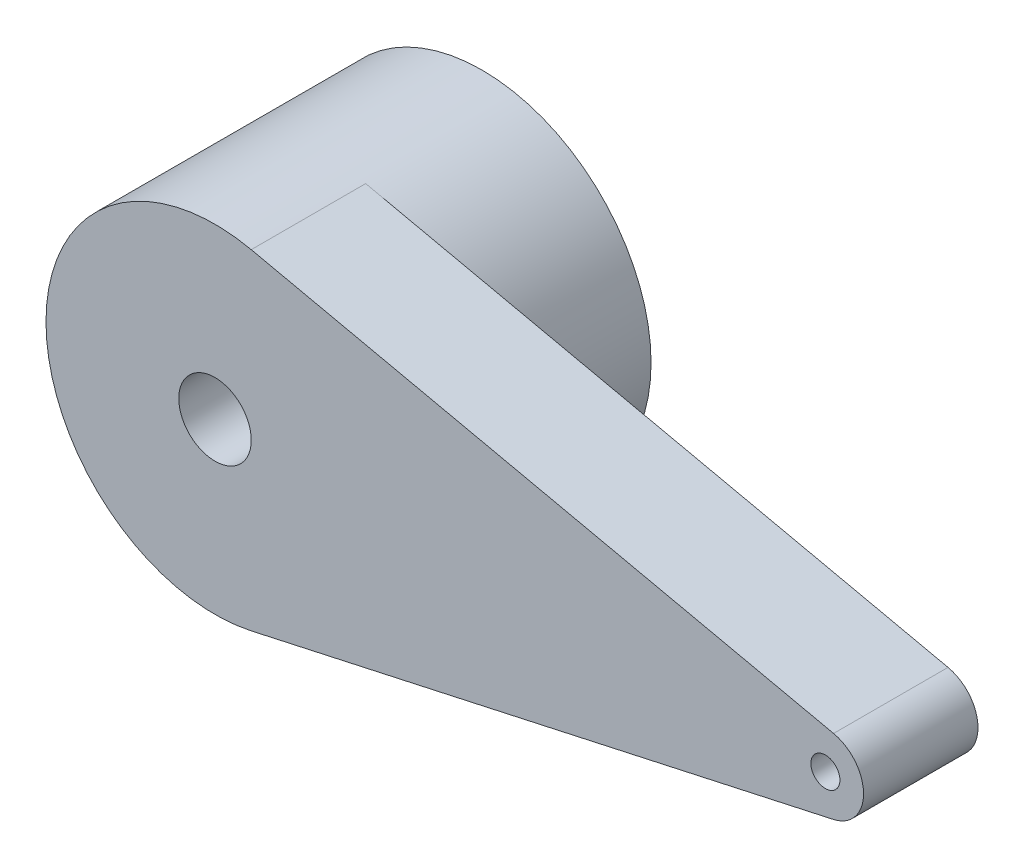
SolidWorks part; units mm, degrees
ref_plane "Front Plane" through (0, 0, 0) normal (0, 0, 1) x (1, 0, 0)
ref_plane "Top Plane" through (0, 0, 0) normal (0, 1, 0) x (1, 0, 0)
ref_plane "Right Plane" through (0, 0, 0) normal (1, 0, 0) x (0, 0, -1)
sketch "Sketch1" plane through (0, 0, 0) normal (0, 0, 1) x (1, 0, 0)
  line L0 (0.9497, 4.327) -> (16.2144, 0.9768)
  line L1 (16.2144, -0.9768) -> (0.9497, -4.327)
  line L2 (0, 0) -> (16, 0) construction
  arc A0 (0.9497, 4.327) -> (0.9497, -4.327) centre (0, 0) ccw
  circle A1 centre (0, 0) radius 0.95
  arc A2 (16.2144, 0.9768) -> (16.2144, -0.9768) centre (16, 0) cw
  circle A3 centre (16, 0) radius 0.381
  circle A4 centre (0, 0) radius 2.43 construction
  dimension "D1" = 1.9
  dimension "D2" = 2
  dimension "D4" = 1
  dimension "D5" = 0.762
  dimension "D6" = 4.86
  dimension "D3" = 16
extrude "Boss-Extrude1" add sketch "Sketch1" along normal blind 3
sketch "Sketch2" plane through (0, 0, 0) normal (0, 0, -1) x (-1, 0, 0)
  circle A0 centre (0, 0) radius 2.43
  circle A1 centre (0, 0) radius 4.43
  arc A2 (-0.9497, -4.327) -> (-0.9497, 4.327) centre (0, 0) ccw construction
  dimension "D1" = 2
extrude "Boss-Extrude2" add sketch "Sketch2" along normal blind 4
